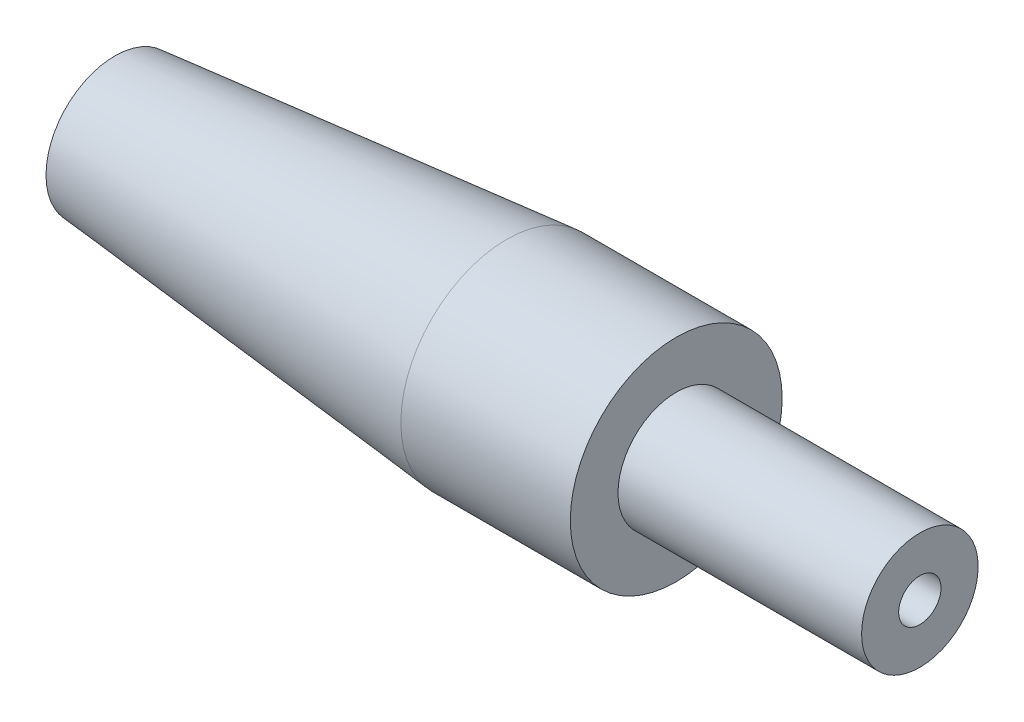
SolidWorks part; units mm, degrees
ref_plane "前视基准面" through (0, 0, 0) normal (0, 0, 1) x (1, 0, 0)
ref_plane "上视基准面" through (0, 0, 0) normal (0, 1, 0) x (1, 0, 0)
ref_plane "右视基准面" through (0, 0, 0) normal (1, 0, 0) x (0, 0, -1)
sketch "草图1" plane through (0, 0, 0) normal (0, 1, 0) x (1, 0, 0)
  line L0 (-52.5974, 0) -> (49.9524, 0) construction
  line L1 (0, 13.0355) -> (0, -15.4504) construction
  line L2 (11.5, 0) -> (11.5, 2.75)
  line L3 (11.5, 2.75) -> (0, 2.75)
  line L4 (0, 2.75) -> (0, 5)
  line L5 (0, 5) -> (-8, 5)
  line L6 (-8, 5) -> (-26.5, 3.25)
  line L7 (-26.5, 3.25) -> (-26.5, 0)
  line L8 (-26.5, 0) -> (11.5, 0)
  dimension "D1" = 2.75
  dimension "D2" = 11.5
  dimension "D3" = 8
  dimension "D4" = 5
  dimension "D5" = 38
  dimension "D6" = 3.25
revolve "旋转2" add sketch "草图1" angle 360 about L0
sketch "草图2" plane through (11.5, 0, 0) normal (1, 0, 0) x (0, 0, -1)
  circle A0 centre (0, 0) radius 1
  dimension "D1" = 2
extrude "切除-拉伸1" cut sketch "草图2" against normal blind 8
